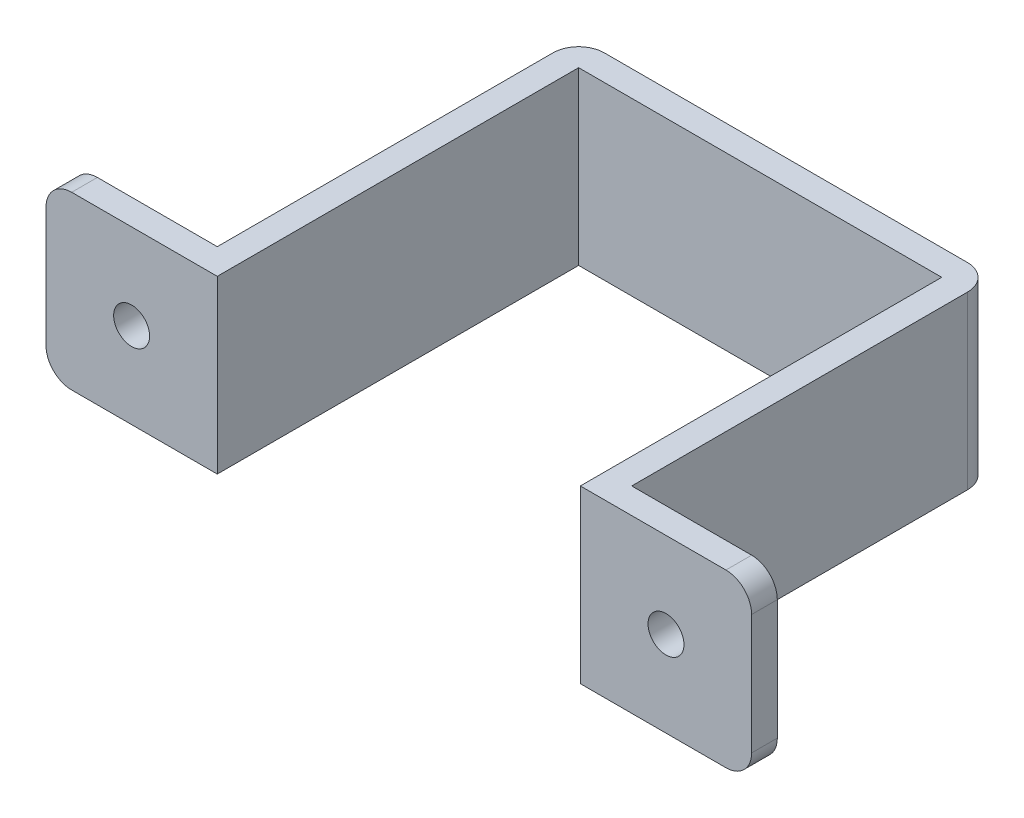
SolidWorks part; units mm, degrees
ref_plane "前视基准面" through (0, 0, 0) normal (0, 0, 1) x (1, 0, 0)
ref_plane "上视基准面" through (0, 0, 0) normal (0, 1, 0) x (1, 0, 0)
ref_plane "右视基准面" through (0, 0, 0) normal (1, 0, 0) x (0, 0, -1)
other "Configuration Table"
sketch "草图1" plane through (0, 0, 0) normal (0, 1, 0) x (1, 0, 0)
  line L0 (-21.2, 6.0133) -> (-21.2, 0)
  line L1 (-21.2, 42.2) -> (21.2, 42.2)
  line L2 (21.2, 42.2) -> (21.2, 6.0133)
  line L3 (24.2, 3) -> (41.2, 3)
  line L4 (41.2, 3) -> (41.2, 0)
  line L5 (41.2, 0) -> (21.2, 0)
  line L7 (0, 42.2) -> (0, 45.2)
  line L8 (-24.2, 45.2) -> (24.2, 45.2)
  line L9 (24.2, 45.2) -> (24.2, 3)
  line L10 (21.2, 6.0133) -> (21.2, 0)
  line L11 (-24.2, 45.2) -> (-24.2, 3)
  line L12 (-41.2, 0) -> (-21.2, 0)
  line L13 (-41.2, 3) -> (-41.2, 0)
  line L14 (-24.2, 3) -> (-41.2, 3)
  line L15 (-21.2, 42.2) -> (-21.2, 6.0133)
  dimension "D1" = 21.2
  dimension "D2" = 42.2
  dimension "D3" = 20
  dimension "D4" = 3
  dimension "D5" = 3
  dimension "D6" = 3
extrude "凸台-拉伸1" add sketch "草图1" along normal blind 20 contours L8 L9 L3 L4 L5 L10 L2 L1 L15 L0 L12 L13 L14 L11
fillet "圆角1" radius 3 2 edges at (-24.2, 10, -45.2) (24.2, 10, -45.2)
fillet "圆角2" radius 3 4 edges at (-41.2, 0, -1.5) (-41.2, 20, -1.5) (41.2, 0, -1.5) (41.2, 20, -1.5)
sketch "草图3" plane through (0, 0, -3) normal (0, 0, -1) x (-1, 0, 0)
  line L0 (-41.2, 17) -> (-41.2, 3) construction
  line L1 (41.2, 17) -> (41.2, 3) construction
  circle A0 centre (31.2, 10) radius 2.1
  circle A1 centre (-31.2, 10) radius 2.1
  dimension "D1" = 4.2
  dimension "D3" = 4.2
  dimension "D2" = 10
  dimension "D4" = 10
extrude "切除-拉伸1" cut sketch "草图3" against normal blind 10
